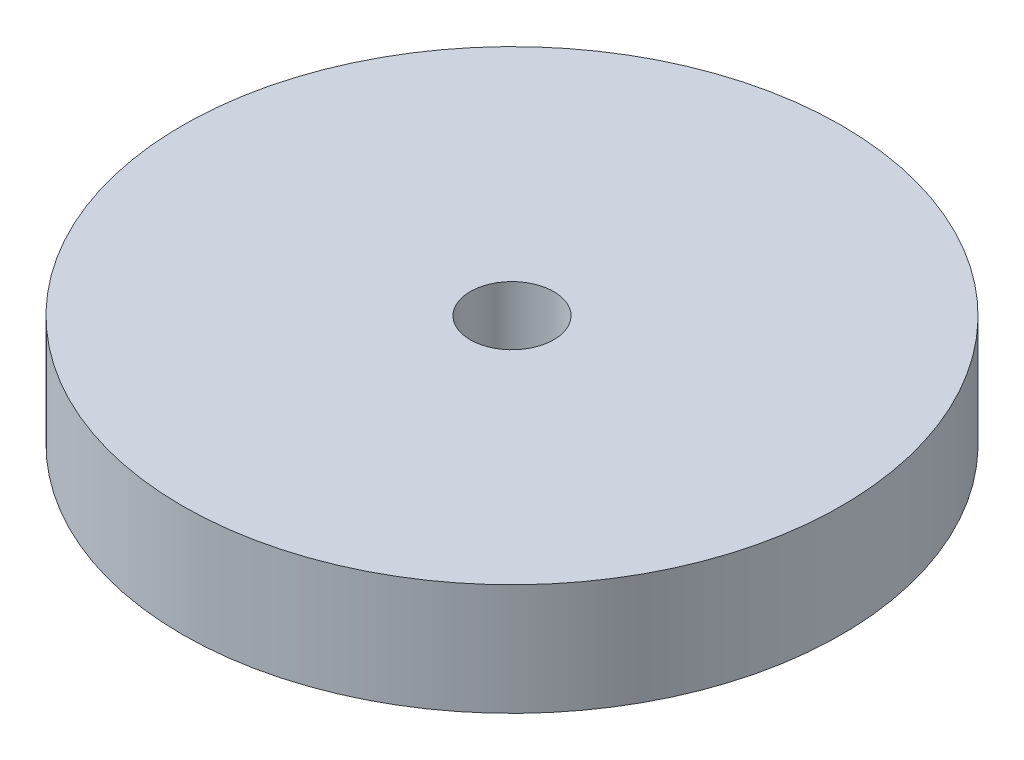
SolidWorks part; units mm, degrees
ref_plane "Front Plane" through (0, 0, 0) normal (0, 0, 1) x (1, 0, 0)
ref_plane "Top Plane" through (0, 0, 0) normal (0, 1, 0) x (1, 0, 0)
ref_plane "Right Plane" through (0, 0, 0) normal (1, 0, 0) x (0, 0, -1)
sketch "Sketch1" plane through (0, 0, 0) normal (0, 1, 0) x (1, 0, 0)
  circle A0 centre (0, 0) radius 35.5
  dimension "D1" = 71
extrude "Boss-Extrude1" add sketch "Sketch1" along normal blind 12
sketch "Sketch2" plane through (0, 12, 0) normal (0, 1, 0) x (1, 0, 0)
  circle A0 centre (0, 0) radius 4.5
  dimension "D1" = 9
extrude "Cut-Extrude1" cut sketch "Sketch2" against normal through all
